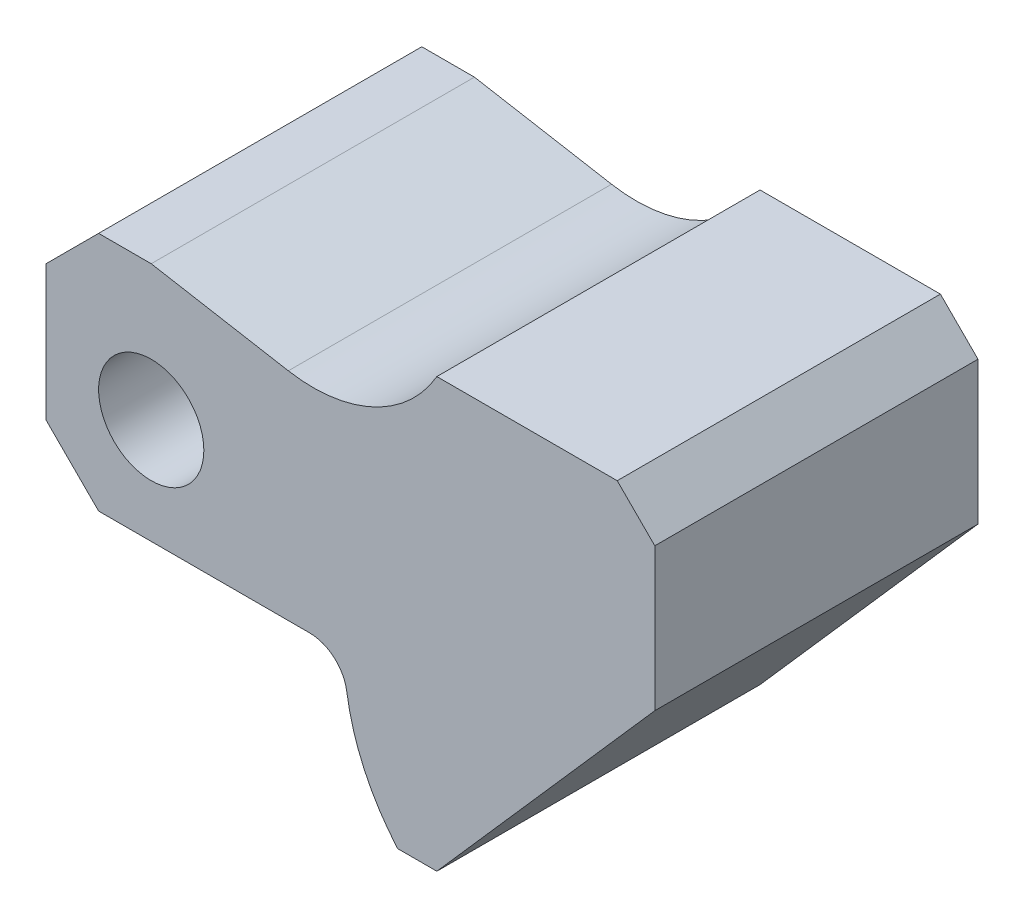
SolidWorks part; units mm, degrees
material "AISI 1020"
ref_plane "Front Plane" through (0, 0, 0) normal (0, 0, 1) x (1, 0, 0)
ref_plane "Top Plane" through (0, 0, 0) normal (0, 1, 0) x (1, 0, 0)
ref_plane "Right Plane" through (0, 0, 0) normal (1, 0, 0) x (0, 0, -1)
sketch "Sketch1" plane through (0, 0, 0) normal (0, 0, 1) x (1, 0, 0)
  line L0 (0, 0) -> (-7, 7)
  line L1 (-7, 7) -> (-7, 25)
  line L2 (-7, 25) -> (0, 32)
  line L6 (74, 33) -> (74, 14)
  line L7 (74, 14) -> (45, -19)
  line L8 (45, -19) -> (39.7881, -19)
  line L9 (28.0666, 0) -> (0, 0)
  line L10 (74, 33) -> (69, 38)
  line L11 (69, 38) -> (45, 38)
  line L12 (0, 32) -> (7, 32)
  line L13 (7, 32) -> (25.2431, 28.7833)
  line L14 (7, -41.8607) -> (7, 32) construction
  line L15 (28.0666, 14) -> (-35.9051, 14) construction
  arc A2 (39.7881, -19) -> (33.0123, -4.2647) centre (61.697, 0) cw
  arc A4 (33.0123, -4.2647) -> (28.0666, 0) centre (28.0666, -5) ccw
  arc A5 (45, 38) -> (25.2431, 28.7833) centre (28.5424, 47.4946) cw
  circle A6 centre (7, 14) radius 7
  point P8 (42.394, -19)
  point P20 (14.0333, 0)
  dimension "D5" = 29
  dimension "D6" = 5
  dimension "D14" = 19
  dimension "D21" = 14
  dimension "D2" = 7
  dimension "D3" = 45
  dimension "D4" = 19
  dimension "D7" = 29
  dimension "D8" = 19
  dimension "D9" = 24
  dimension "D10" = 45
  dimension "D11" = 5
  dimension "D12" = 29
  dimension "D13" = 57
  dimension "D15" = 10
  dimension "D17" = 32
  dimension "D16" = 45
  dimension "D18" = 81
  dimension "D19" = 14
  dimension "D20" = 14
extrude "Boss-Extrude1" add sketch "Sketch1" along normal mid plane 43
equation "\"B\" = 57"
equation "\"A\" = 81"
equation "\"c\" = 43"
equation "\"D1@Boss-Extrude1\"=\"c\""
equation "\"D13@Sketch1\"=\"B\""
equation "\"D18@Sketch1\"=\"A\""
